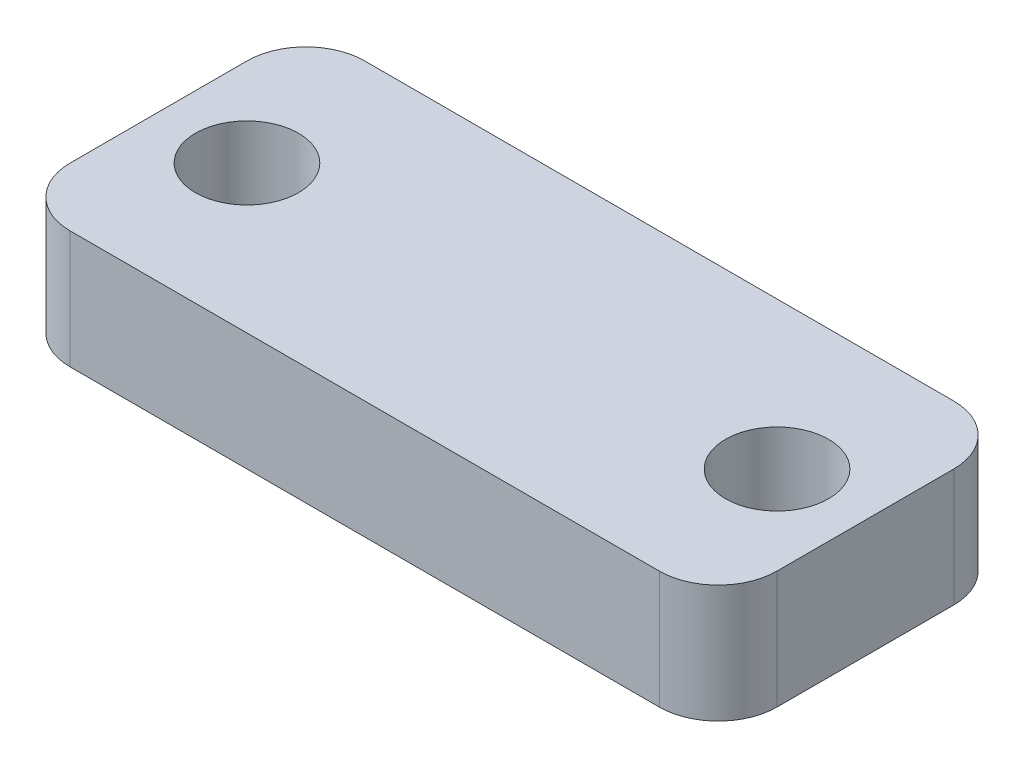
SolidWorks part; units mm, degrees
ref_plane "Plano frontal" through (0, 0, 0) normal (0, 0, 1) x (1, 0, 0)
ref_plane "Plano superior" through (0, 0, 0) normal (0, 1, 0) x (1, 0, 0)
ref_plane "Plano direito" through (0, 0, 0) normal (1, 0, 0) x (0, 0, -1)
sketch "Esboço1" plane through (0, 0, 0) normal (0, 1, 0) x (1, 0, 0)
  line L1 (-12, 5) -> (12, 5)
  line L2 (-12, 5) -> (-12, -5)
  line L3 (-12, -5) -> (12, -5)
  line L4 (12, 5) -> (12, -5)
  line L5 (-12, 5) -> (12, -5) construction
  line L6 (-12, -5) -> (12, 5) construction
  point P0 (0, 0)
  dimension "D1" = 10
  dimension "D2" = 24
extrude "Ressalto-extrusão1" add sketch "Esboço1" along normal mid plane 4
sketch "Esboço2" plane through (0, 2, 0) normal (0, 1, 0) x (1, 0, 0)
  line L0 (0, 5) -> (0, -5) construction
  line L1 (12, 5) -> (-12, 5) construction
  line L2 (-12, -5) -> (12, -5) construction
  line L3 (12, 0) -> (-12, 0) construction
  line L4 (12, -5) -> (12, 5) construction
  line L5 (-12, 5) -> (-12, -5) construction
  circle A0 centre (-9, 0) radius 1.75
  dimension "D2" = 3.5
  dimension "D1" = 9
extrude "Corte-extrusão1" cut sketch "Esboço2" against normal through all
mirror "Espelhar1" about plane through (0, 0, 0) normal (1, 0, 0) of "Corte-extrusão1"
fillet "Filete1" radius 2 4 edges at (12, 0, 5) (12, 0, -5) (-12, 0, 5) (-12, 0, -5)
